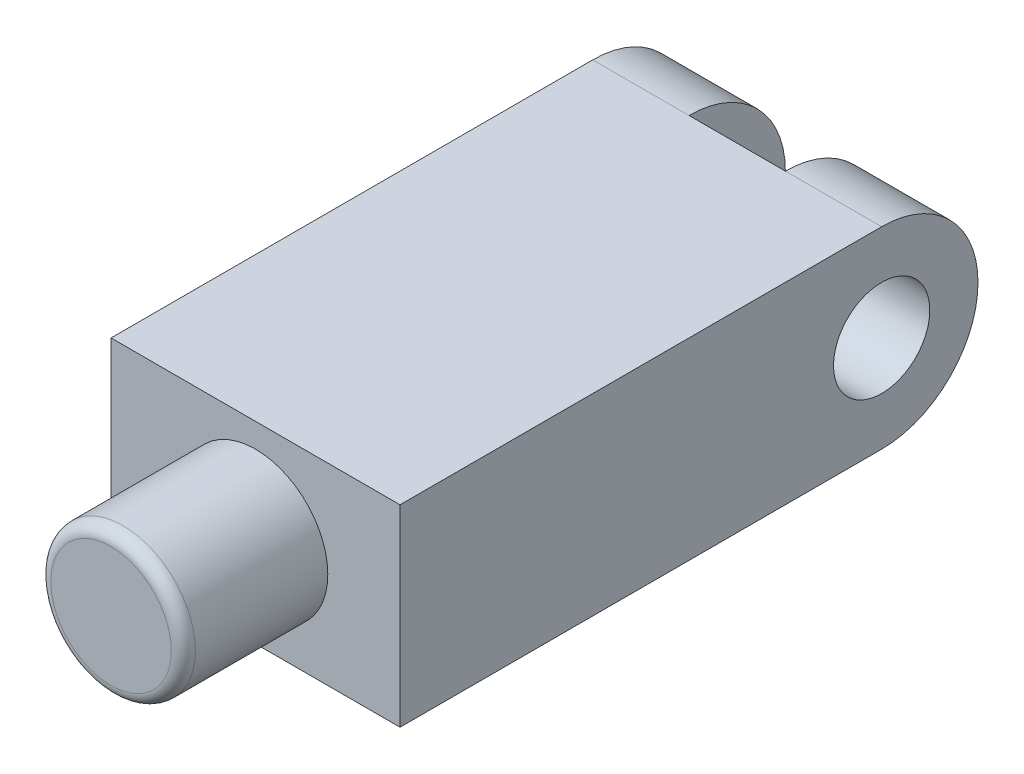
SolidWorks part; units mm, degrees
ref_plane "정면" through (0, 0, 0) normal (0, 0, 1) x (1, 0, 0)
ref_plane "윗면" through (0, 0, 0) normal (0, 1, 0) x (1, 0, 0)
ref_plane "우측면" through (0, 0, 0) normal (1, 0, 0) x (0, 0, -1)
sketch "스케치1" plane through (0, 0, 0) normal (0, 0, 1) x (1, 0, 0)
  line L1 (50, -15) -> (-10, -15)
  line L2 (50, -15) -> (50, 25)
  line L3 (50, 25) -> (-10, 25)
  line L4 (-10, -15) -> (-10, 25)
  line L5 (50, -15) -> (-10, 25) construction
  line L6 (50, 25) -> (-10, -15) construction
  dimension "D1" = 40
  dimension "D2" = 60
extrude "보스-돌출1" add sketch "스케치1" along normal blind 100
sketch "스케치6" plane through (50, 0, 0) normal (1, 0, 0) x (0, 0, -1)
  line L0 (0, -15) -> (0, 25) construction
  circle A0 centre (0, 5) radius 20
extrude "보스-돌출2" add sketch "스케치6" against normal blind 20
sketch "스케치7" plane through (-10, 0, 0) normal (-1, 0, 0) x (0, 0, 1)
  line L0 (0, 25) -> (0, -15) construction
  circle A0 centre (0, 5) radius 20
extrude "보스-돌출3" add sketch "스케치7" against normal blind 20
sketch "스케치8" plane through (-10, 0, 0) normal (-1, 0, 0) x (0, 0, 1)
  circle A0 centre (0, 5) radius 10
  dimension "D1" = 20
extrude "컷-돌출1" cut sketch "스케치8" against normal through all both and the other way through all
ref_plane "평면1" through (0, 0, 0) normal (0, 0, 1) x (1, 0, 0)
sketch "스케치9" plane through (30, 0, 0) normal (-1, 0, 0) x (0, 0, 1)
  circle A0 centre (0, 5) radius 20
  dimension "D1" = 40
extrude "컷-돌출2" cut sketch "스케치9" along normal blind 20
sketch "스케치10" plane through (0, 0, 100) normal (0, 0, 1) x (1, 0, 0)
  line L0 (-10, 25) -> (50, -15)
  line L1 (50, 25) -> (-10, -15)
  circle A0 centre (20, 5) radius 15
  dimension "D1" = 30
extrude "보스-돌출4" add sketch "스케치10" along normal blind 30 contours A0
fillet "필렛1" radius 2.5 1 edges at (35, 5, 130)
